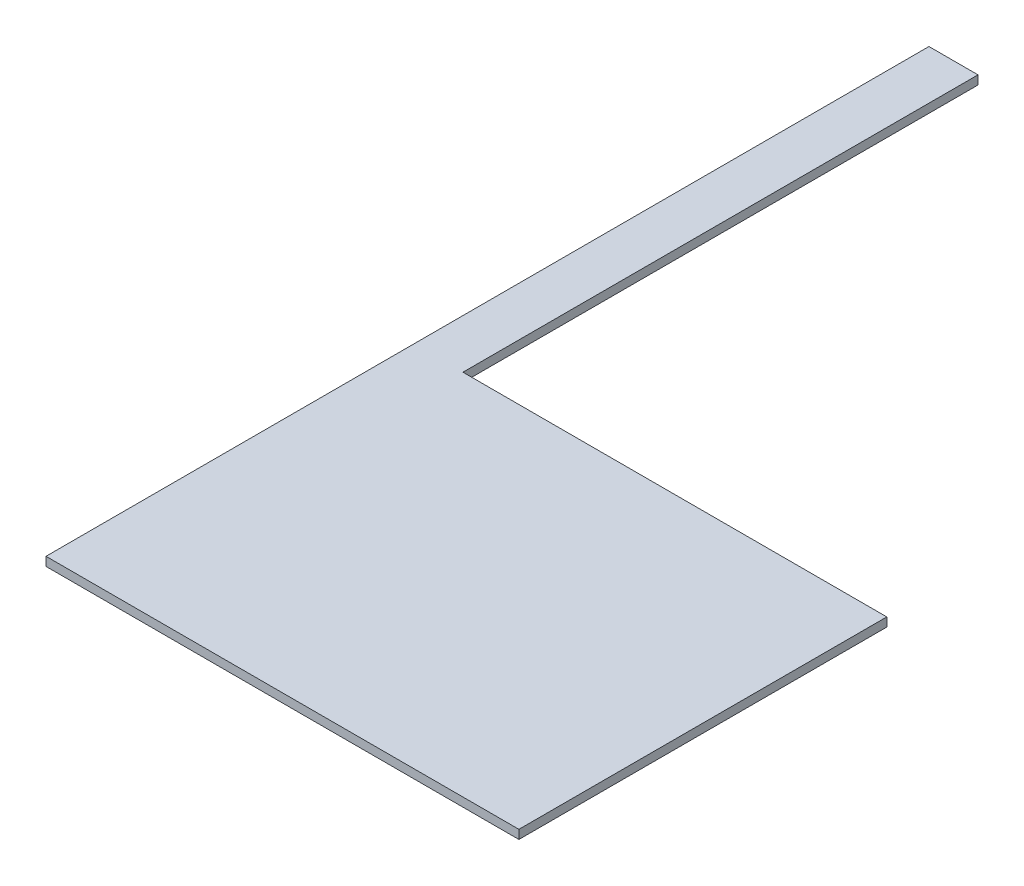
SolidWorks part; units mm, degrees
ref_plane "Front Plane" through (0, 0, 0) normal (0, 0, 1) x (1, 0, 0)
ref_plane "Top Plane" through (0, 0, 0) normal (0, 1, 0) x (1, 0, 0)
ref_plane "Right Plane" through (0, 0, 0) normal (1, 0, 0) x (0, 0, -1)
sketch "Sketch1" plane through (0, 0, 0) normal (0, 1, 0) x (1, 0, 0)
  line L0 (-489.7438, 381) -> (-489.7438, 1447.8)
  line L1 (-489.7438, -381) -> (489.7437, -381)
  line L2 (-489.7438, -381) -> (-489.7438, 381)
  line L4 (489.7437, -381) -> (489.7437, 381)
  line L5 (-489.7438, -381) -> (489.7437, 381) construction
  line L6 (-489.7438, 381) -> (489.7437, -381) construction
  line L7 (-489.7438, 1447.8) -> (-388.1438, 1447.8)
  line L8 (-388.1438, 1447.8) -> (-388.1438, 381)
  line L9 (-388.1438, 381) -> (489.7437, 381)
  point P0 (0, 0)
  dimension "D1" = 762
  dimension "D2" = 979.4875
  dimension "D3" = 1066.8
  dimension "D4" = 101.6
extrude "Boss-Extrude1" add sketch "Sketch1" along normal blind 18.2562
